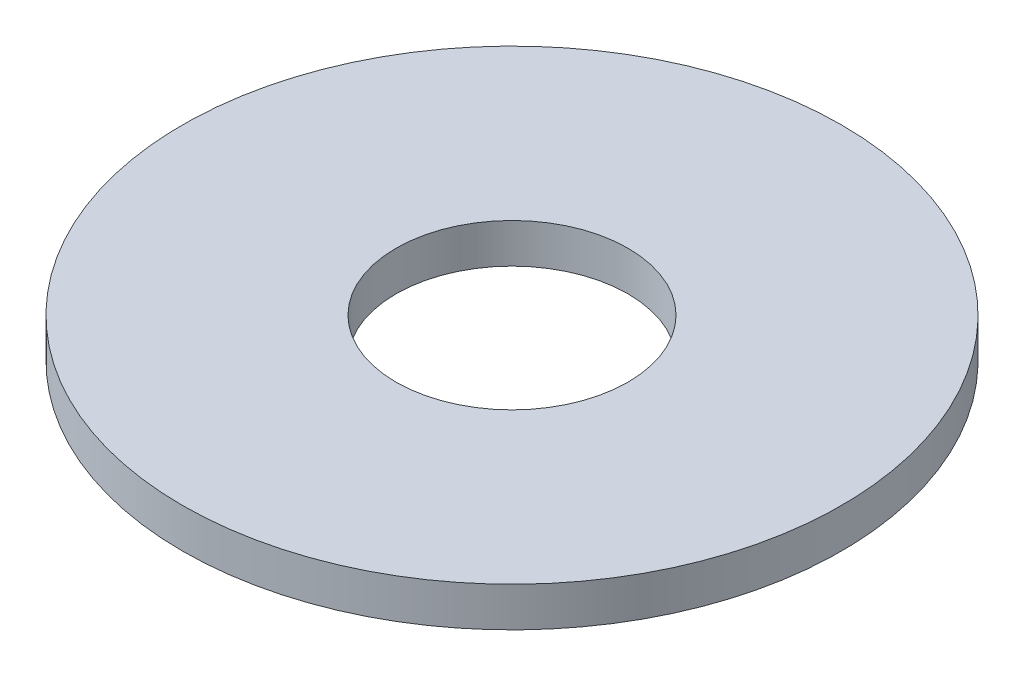
SolidWorks part; units mm, degrees
ref_plane "Front Plane" through (0, 0, 0) normal (0, 0, 1) x (1, 0, 0)
ref_plane "Top Plane" through (0, 0, 0) normal (0, 1, 0) x (1, 0, 0)
ref_plane "Right Plane" through (0, 0, 0) normal (1, 0, 0) x (0, 0, -1)
sketch "Sketch1" plane through (0, 0, 0) normal (0, 1, 0) x (1, 0, 0)
  circle A0 centre (0, 0) radius 12.5
  circle A2 centre (0, 0) radius 4.4
  dimension "D1" = 25
  dimension "D2" = 8.8
extrude "Boss-Extrude1" add sketch "Sketch1" along normal blind 1.5
